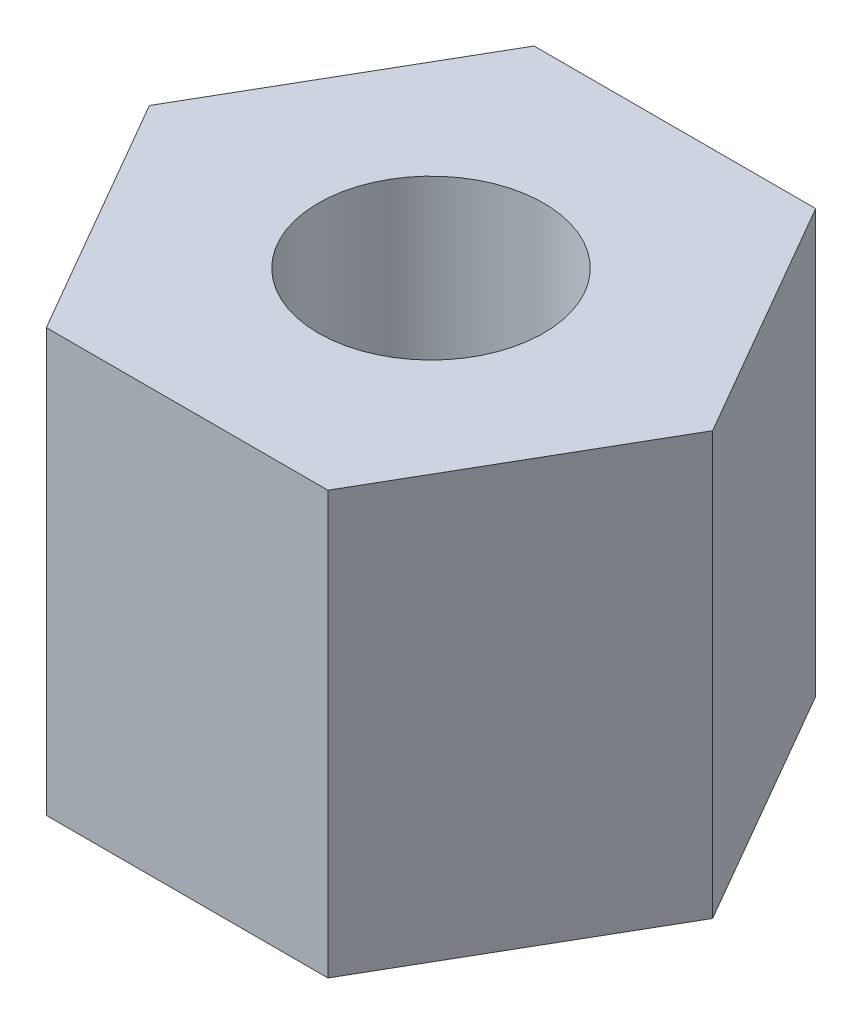
SolidWorks part; units mm, degrees
ref_plane "Front Plane" through (0, 0, 0) normal (0, 0, 1) x (1, 0, 0)
ref_plane "Top Plane" through (0, 0, 0) normal (0, 1, 0) x (1, 0, 0)
ref_plane "Right Plane" through (0, 0, 0) normal (1, 0, 0) x (0, 0, -1)
sketch "Sketch1" plane through (0, 0, 0) normal (0, 1, 0) x (1, 0, 0)
  line L1 (10, 0) -> (5, 8.6603)
  line L2 (5, 8.6603) -> (-5, 8.6603)
  line L3 (-5, 8.6603) -> (-10, 0)
  line L4 (-10, 0) -> (-5, -8.6603)
  line L5 (-5, -8.6603) -> (5, -8.6603)
  line L6 (5, -8.6603) -> (10, 0)
  circle A0 centre (0, 0) radius 8.6603 construction
  circle A1 centre (0, 0) radius 4
  dimension "D2" = 8
  dimension "D1" = 10
extrude "Boss-Extrude1" add sketch "Sketch1" along normal blind 15 contours A1 | L3 L4 L5 L6 L1 L2
